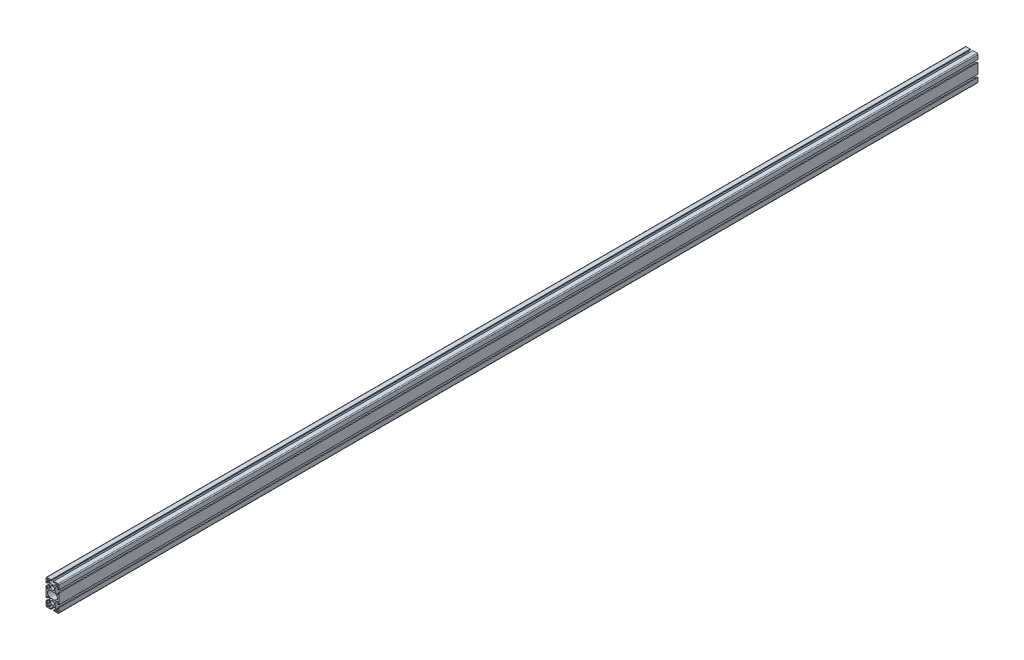
SolidWorks part; units mm, degrees
ref_plane "Front Plane" through (0, 0, 0) normal (0, 0, 1) x (1, 0, 0)
ref_plane "Top Plane" through (0, 0, 0) normal (0, 1, 0) x (1, 0, 0)
ref_plane "Right Plane" through (0, 0, 0) normal (1, 0, 0) x (0, 0, -1)
sketch "Sketch1" plane through (0, 0, 0) normal (0, 0, 1) x (1, 0, 0)
  line L0 (-17, -40) -> (-4.1, -40)
  line L1 (-4.1, -40) -> (-4.1, -37)
  line L2 (-4.1, -37) -> (-10.5, -37)
  line L3 (-10.5, -37) -> (-10.5, -33.6627)
  line L4 (-10.0314, -32.5314) -> (-7.4645, -29.9645)
  line L5 (-3.9289, -28.5) -> (3.9289, -28.5)
  line L6 (7.4645, -29.9645) -> (10.0314, -32.5314)
  line L7 (10.5, -33.6627) -> (10.5, -37)
  line L8 (10.5, -37) -> (4.1, -37)
  line L9 (4.1, -37) -> (4.1, -40)
  line L10 (4.1, -40) -> (17, -40)
  line L11 (20, -37) -> (20, -24.1)
  line L12 (20, -24.1) -> (17, -24.1)
  line L13 (17, -24.1) -> (17, -30.5)
  line L14 (17, -30.5) -> (13.6627, -30.5)
  line L15 (12.5314, -30.0314) -> (9.9645, -27.4645)
  line L16 (8.5, -23.9289) -> (8.5, -16.0711)
  line L17 (9.9645, -12.5355) -> (12.5314, -9.9686)
  line L18 (13.6627, -9.5) -> (17, -9.5)
  line L19 (17, -9.5) -> (17, -15.9)
  line L20 (17, -15.9) -> (20, -15.9)
  line L21 (20, -15.9) -> (20, 15.9)
  line L22 (20, 15.9) -> (17, 15.9)
  line L23 (17, 15.9) -> (17, 9.5)
  line L24 (17, 9.5) -> (13.6627, 9.5)
  line L25 (12.5314, 9.9686) -> (9.9645, 12.5355)
  line L26 (8.5, 16.0711) -> (8.5, 23.9289)
  line L27 (9.9645, 27.4645) -> (12.5314, 30.0314)
  line L28 (13.6627, 30.5) -> (17, 30.5)
  line L29 (17, 30.5) -> (17, 24.1)
  line L30 (17, 24.1) -> (20, 24.1)
  line L31 (20, 24.1) -> (20, 37)
  line L32 (17, 40) -> (4.1, 40)
  line L33 (4.1, 40) -> (4.1, 37)
  line L34 (4.1, 37) -> (10.5, 37)
  line L35 (10.5, 37) -> (10.5, 33.6627)
  line L36 (10.0314, 32.5314) -> (7.4645, 29.9645)
  line L37 (3.9289, 28.5) -> (-3.9289, 28.5)
  line L38 (-7.4645, 29.9645) -> (-10.0314, 32.5314)
  line L39 (-10.5, 33.6627) -> (-10.5, 37)
  line L40 (-10.5, 37) -> (-4.1, 37)
  line L41 (-4.1, 37) -> (-4.1, 40)
  line L42 (-4.1, 40) -> (-17, 40)
  line L43 (-20, 37) -> (-20, 24.1)
  line L44 (-20, 24.1) -> (-17, 24.1)
  line L45 (-17, 24.1) -> (-17, 30.5)
  line L46 (-17, 30.5) -> (-13.6627, 30.5)
  line L47 (-12.5314, 30.0314) -> (-9.9645, 27.4645)
  line L48 (-8.5, 23.9289) -> (-8.5, 16.0711)
  line L49 (-9.9645, 12.5355) -> (-12.5314, 9.9686)
  line L50 (-13.6627, 9.5) -> (-17, 9.5)
  line L51 (-17, 9.5) -> (-17, 15.9)
  line L52 (-17, 15.9) -> (-20, 15.9)
  line L53 (-20, 15.9) -> (-20, -15.9)
  line L54 (-20, -15.9) -> (-17, -15.9)
  line L55 (-17, -15.9) -> (-17, -9.5)
  line L56 (-17, -9.5) -> (-13.6627, -9.5)
  line L57 (-12.5314, -9.9686) -> (-9.9645, -12.5355)
  line L58 (-8.5, -16.0711) -> (-8.5, -23.9289)
  line L59 (-9.9645, -27.4645) -> (-12.5314, -30.0314)
  line L60 (-13.6627, -30.5) -> (-17, -30.5)
  line L61 (-17, -30.5) -> (-17, -24.1)
  line L62 (-17, -24.1) -> (-20, -24.1)
  line L63 (-20, -24.1) -> (-20, -37)
  line L64 (-14.2426, -4.2426) -> (-9.9497, -8.5355)
  line L65 (-6.4142, -10) -> (6.4142, -10)
  line L66 (9.9497, -8.5355) -> (14.2426, -4.2426)
  line L67 (14.2426, 4.2426) -> (9.9497, 8.5355)
  line L68 (6.4142, 10) -> (-6.4142, 10)
  line L69 (-9.9497, 8.5355) -> (-14.2426, 4.2426)
  arc A0 (-20, -37) -> (-17, -40) centre (-17, -37) ccw
  arc A1 (-10.5, -33.6627) -> (-10.0314, -32.5314) centre (-8.9, -33.6627) cw
  arc A2 (-7.4645, -29.9645) -> (-3.9289, -28.5) centre (-3.9289, -33.5) cw
  arc A3 (3.9289, -28.5) -> (7.4645, -29.9645) centre (3.9289, -33.5) cw
  arc A4 (10.0314, -32.5314) -> (10.5, -33.6627) centre (8.9, -33.6627) cw
  arc A5 (17, -40) -> (20, -37) centre (17, -37) ccw
  arc A6 (13.6627, -30.5) -> (12.5314, -30.0314) centre (13.6627, -28.9) cw
  arc A7 (9.9645, -27.4645) -> (8.5, -23.9289) centre (13.5, -23.9289) cw
  arc A8 (8.5, -16.0711) -> (9.9645, -12.5355) centre (13.5, -16.0711) cw
  arc A9 (12.5314, -9.9686) -> (13.6627, -9.5) centre (13.6627, -11.1) cw
  arc A10 (13.6627, 9.5) -> (12.5314, 9.9686) centre (13.6627, 11.1) cw
  arc A11 (9.9645, 12.5355) -> (8.5, 16.0711) centre (13.5, 16.0711) cw
  arc A12 (8.5, 23.9289) -> (9.9645, 27.4645) centre (13.5, 23.9289) cw
  arc A13 (12.5314, 30.0314) -> (13.6627, 30.5) centre (13.6627, 28.9) cw
  arc A14 (20, 37) -> (17, 40) centre (17, 37) ccw
  arc A15 (10.5, 33.6627) -> (10.0314, 32.5314) centre (8.9, 33.6627) cw
  arc A16 (7.4645, 29.9645) -> (3.9289, 28.5) centre (3.9289, 33.5) cw
  arc A17 (-3.9289, 28.5) -> (-7.4645, 29.9645) centre (-3.9289, 33.5) cw
  arc A18 (-10.0314, 32.5314) -> (-10.5, 33.6627) centre (-8.9, 33.6627) cw
  arc A19 (-17, 40) -> (-20, 37) centre (-17, 37) ccw
  arc A20 (-13.6627, 30.5) -> (-12.5314, 30.0314) centre (-13.6627, 28.9) cw
  arc A21 (-9.9645, 27.4645) -> (-8.5, 23.9289) centre (-13.5, 23.9289) cw
  arc A22 (-8.5, 16.0711) -> (-9.9645, 12.5355) centre (-13.5, 16.0711) cw
  arc A23 (-12.5314, 9.9686) -> (-13.6627, 9.5) centre (-13.6627, 11.1) cw
  arc A24 (-13.6627, -9.5) -> (-12.5314, -9.9686) centre (-13.6627, -11.1) cw
  arc A25 (-9.9645, -12.5355) -> (-8.5, -16.0711) centre (-13.5, -16.0711) cw
  arc A26 (-8.5, -23.9289) -> (-9.9645, -27.4645) centre (-13.5, -23.9289) cw
  arc A27 (-12.5314, -30.0314) -> (-13.6627, -30.5) centre (-13.6627, -28.9) cw
  circle A28 centre (15, 35) radius 2.5
  circle A29 centre (15, -35) radius 2.5
  circle A30 centre (0, 20) radius 6
  circle A31 centre (0, -20) radius 6
  arc A32 (-14.2426, 4.2426) -> (-14.2426, -4.2426) centre (-10, 0) ccw
  arc A33 (-9.9497, -8.5355) -> (-6.4142, -10) centre (-6.4142, -5) ccw
  arc A34 (6.4142, -10) -> (9.9497, -8.5355) centre (6.4142, -5) ccw
  arc A35 (14.2426, -4.2426) -> (14.2426, 4.2426) centre (10, 0) ccw
  arc A36 (9.9497, 8.5355) -> (6.4142, 10) centre (6.4142, 5) ccw
  arc A37 (-6.4142, 10) -> (-9.9497, 8.5355) centre (-6.4142, 5) ccw
  circle A38 centre (-15, 35) radius 2.5
  circle A39 centre (-15, -35) radius 2.5
  dimension "D1" = 40
  dimension "D2" = 80
extrude "Boss-Extrude1" add sketch "Sketch1" against normal blind 2860
